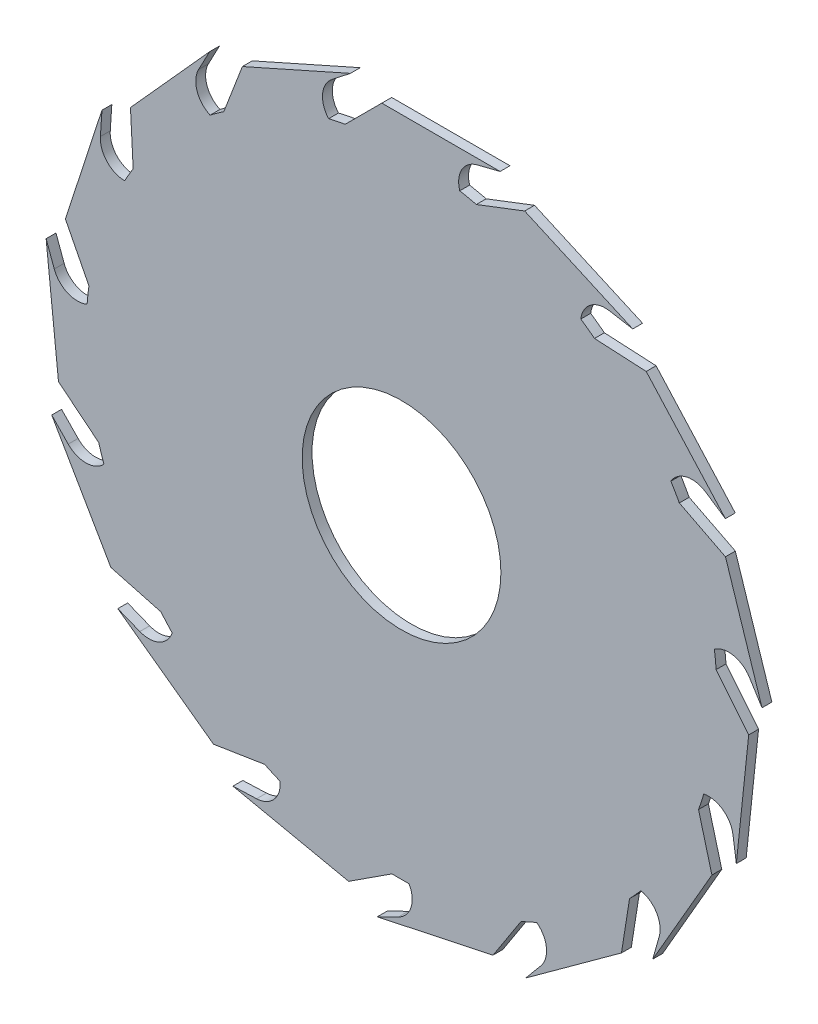
SolidWorks part; units mm, degrees
ref_plane "Front Plane" through (0, 0, 0) normal (0, 0, 1) x (1, 0, 0)
ref_plane "Top Plane" through (0, 0, 0) normal (0, 1, 0) x (1, 0, 0)
ref_plane "Right Plane" through (0, 0, 0) normal (1, 0, 0) x (0, 0, -1)
sketch "Sketch1" plane through (0, 0, 0) normal (0, 0, 1) x (1, 0, 0)
  circle A0 centre (0, 0) radius 50.8
  dimension "D1" = 101.6
extrude "Boss-Extrude1" add sketch "Sketch1" along normal blind 1.5875 contours A0
sketch "Sketch2" plane through (0, 0, 1.5875) normal (0, 0, 1) x (1, 0, 0)
  circle A0 centre (0, 0) radius 16.002
  dimension "D1" = 32.004
extrude "Cut-Extrude1" cut sketch "Sketch2" against normal up to next
sketch "Sketch4" plane through (0, 0, 1.5875) normal (0, 0, 1) x (1, 0, 0)
  line L0 (-9.525, 49.53) -> (-3.175, 55.88)
  line L1 (-3.175, 55.88) -> (15.875, 55.88)
  line L2 (15.875, 55.88) -> (12.1813, 54.9459)
  line L3 (9.525, 49.53) -> (-9.525, 49.53)
  arc A0 (12.1813, 54.9459) -> (9.525, 49.53) centre (13.1512, 51.1108) ccw
  point P6 (0, 0)
  point P8 (0, 49.53)
  point P9 (0, 0)
  dimension "D1" = 3.81
  dimension "D7" = 1.5808
  dimension "D2" = 19.05
  dimension "D3" = 6.35
  dimension "D4" = 19.05
  dimension "D5" = 55.88
  dimension "D6" = 45
extrude "Boss-Extrude2" add sketch "Sketch4" against normal up to surface (1.5875 mm away) up to face at (16.002, 0, 0)
pattern_circular "CirPattern1" count 15 over 360 about axis through (0, 0, 0) along (0, 0, 1) of "Boss-Extrude2"
